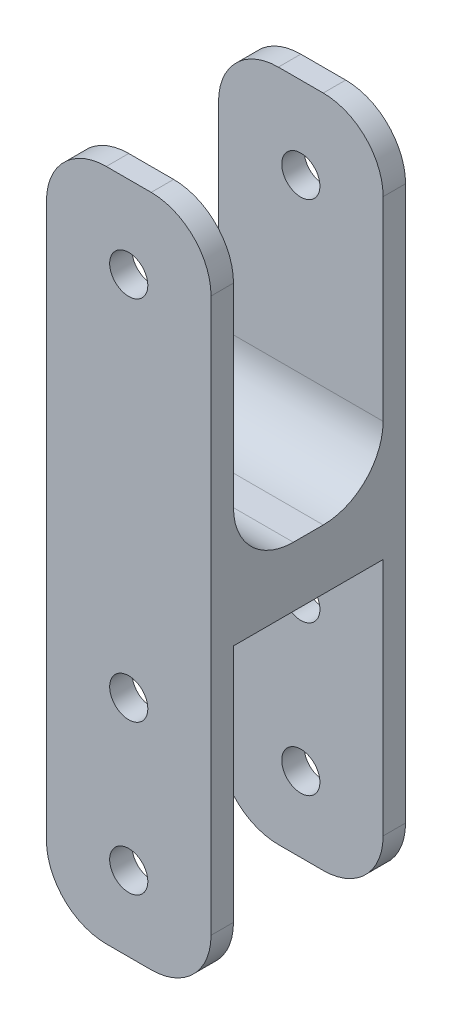
SolidWorks part; units mm, degrees
ref_plane "Спереди" through (0, 0, 0) normal (0, 0, 1) x (1, 0, 0)
ref_plane "Сверху" through (0, 0, 0) normal (0, 1, 0) x (1, 0, 0)
ref_plane "Справа" through (0, 0, 0) normal (1, 0, 0) x (0, 0, -1)
sketch "Эскиз1" plane through (0, 0, 0) normal (1, 0, 0) x (0, 0, -1)
  line L1 (10.2062, 0) -> (10.2062, -40)
  line L2 (10.2062, -40) -> (13.2062, -40)
  line L3 (13.2062, -40) -> (13.2062, 50)
  line L4 (13.2062, 50) -> (10.2062, 50)
  line L5 (10.2062, 50) -> (10.2062, 16)
  line L7 (-9.7938, 16) -> (-9.7938, 50)
  line L8 (-9.7938, 50) -> (-12.7938, 50)
  line L9 (-12.7938, 50) -> (-12.7938, -40)
  line L10 (-12.7938, -40) -> (-9.7938, -40)
  line L11 (-9.7938, -40) -> (-9.7938, 0)
  line L12 (-9.7938, 0) -> (10.2062, 0)
  line L13 (-1.7938, 8) -> (2.2062, 8)
  arc A0 (2.2062, 8) -> (10.2062, 16) centre (2.2062, 16) ccw
  arc A1 (-1.7938, 8) -> (-9.7938, 16) centre (-1.7938, 16) cw
  point P15 (10.2062, 8)
  point P18 (-9.7938, 8)
  dimension "D11" = 8
  dimension "D1" = 42
  dimension "D2" = 20
  dimension "D3" = 3
  dimension "D4" = 3
  dimension "D5" = 3
  dimension "D6" = 3
  dimension "D7" = 40
  dimension "D8" = 40
  dimension "D9" = 8
  dimension "D10" = 42
extrude "Бобышка-Вытянуть1" add sketch "Эскиз1" along normal blind 22
sketch "Эскиз2" plane through (0, 0, 12.7938) normal (0, 0, 1) x (1, 0, 0)
  line L0 (11, -40.8508) -> (11, 54.9976) construction
  line L1 (22, -40) -> (0, -40) construction
  circle A0 centre (11, -30) radius 2.55
  circle A1 centre (11, -10) radius 2.55
  circle A2 centre (11, 39) radius 2.55
  dimension "D1" = 5.1
  dimension "D2" = 5.1
  dimension "D4" = 20
  dimension "D5" = 5.1
  dimension "D6" = 49
  dimension "D3" = 10
extrude "Вырез-Вытянуть1" cut sketch "Эскиз2" against normal through all
fillet "Скругление1" radius 8 8 edges at (0, -40, -11.7062) (22, -40, -11.7062) (22, -40, 11.2938) (0, -40, 11.2938) (0, 50, -11.7062) (22, 50, -11.7062) (22, 50, 11.2938) (0, 50, 11.2938)
